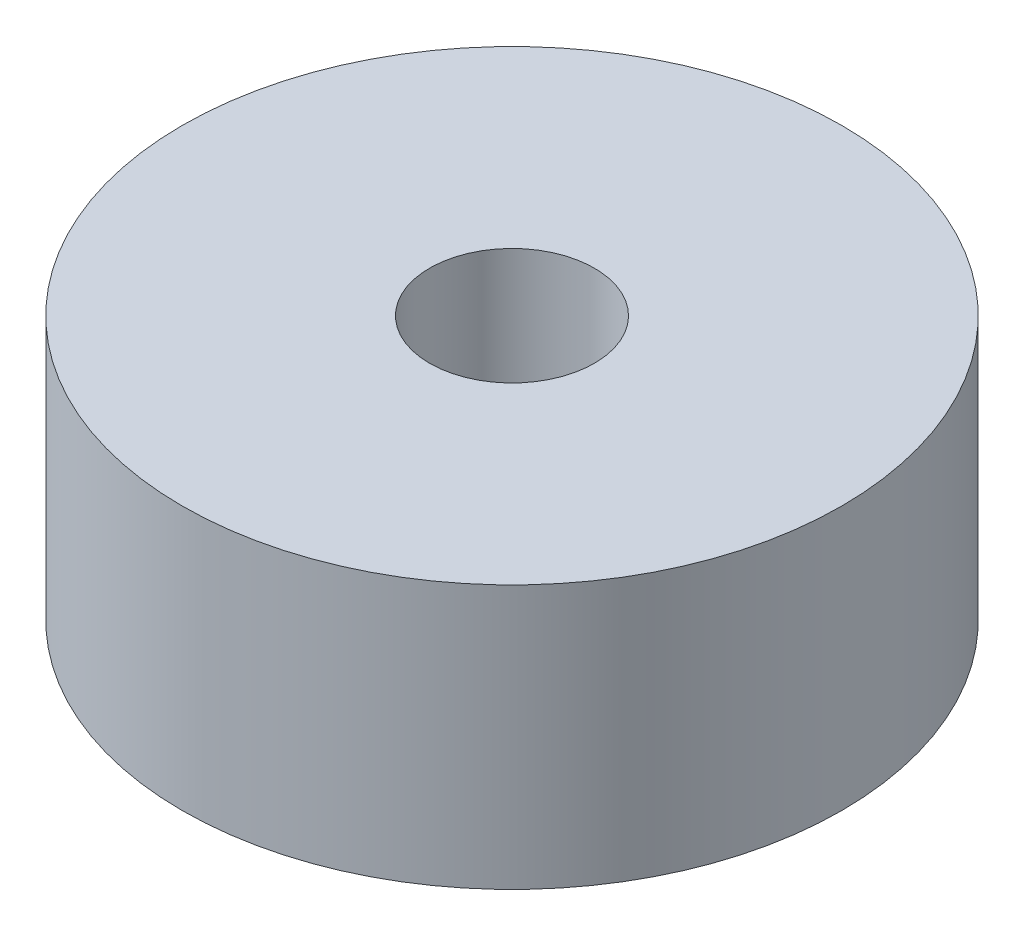
SolidWorks part; units mm, degrees
ref_plane "Front" through (0, 0, 0) normal (0, 0, 1) x (1, 0, 0)
ref_plane "Top" through (0, 0, 0) normal (0, 1, 0) x (1, 0, 0)
ref_plane "Right" through (0, 0, 0) normal (1, 0, 0) x (0, 0, -1)
sketch "Sketch1" plane through (0, 0, 0) normal (0, 1, 0) x (1, 0, 0)
  circle A0 centre (0, 0) radius 100
  circle A1 centre (0, 0) radius 25
  dimension "D1" = 50
  dimension "D2" = 200
extrude "Boss-Extrude1" add sketch "Sketch1" along normal blind 80
